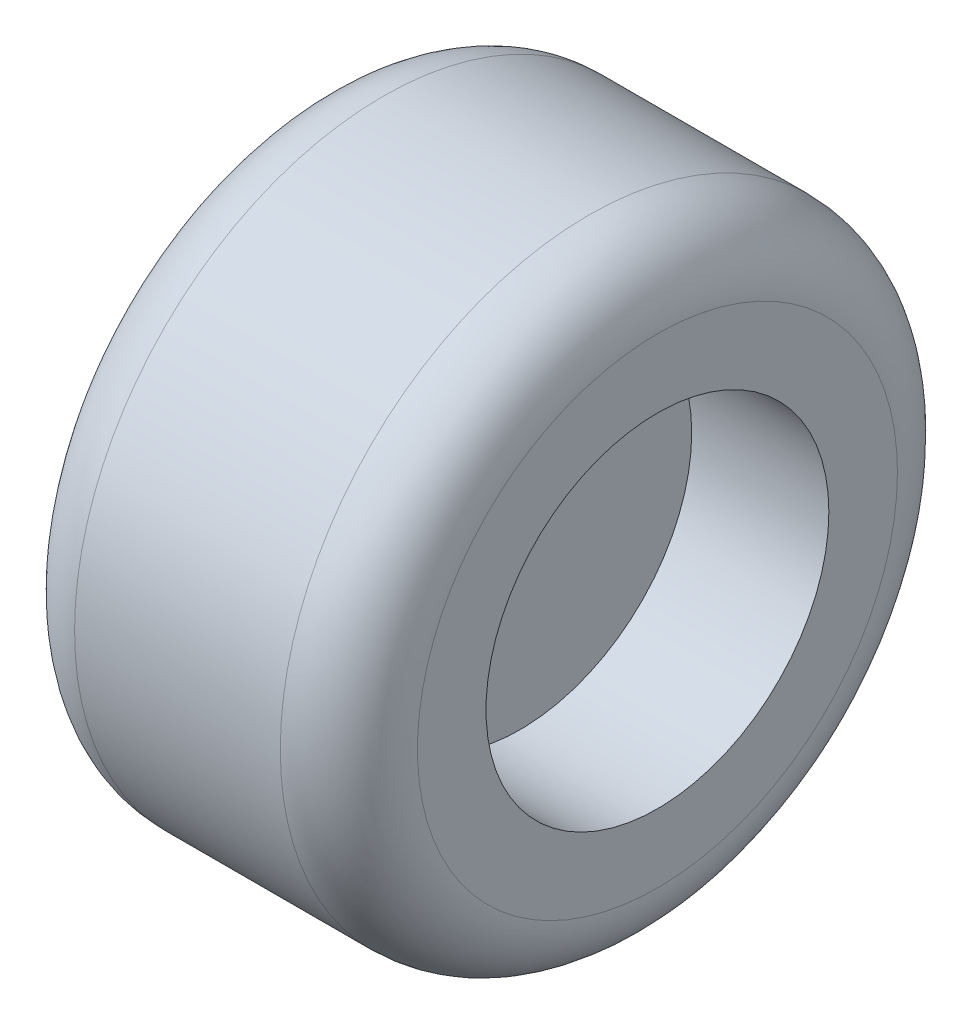
SolidWorks part; units mm, degrees
ref_plane "Front Plane" through (0, 0, 0) normal (0, 0, 1) x (1, 0, 0)
ref_plane "Top Plane" through (0, 0, 0) normal (0, 1, 0) x (1, 0, 0)
ref_plane "Right Plane" through (0, 0, 0) normal (1, 0, 0) x (0, 0, -1)
sketch "Sketch1" plane through (0, 0, 0) normal (1, 0, 0) x (0, 0, -1)
  circle A0 centre (0, 0) radius 22.5
  dimension "D1" = 45
extrude "Boss-Extrude1" add sketch "Sketch1" along normal blind 25
sketch "Sketch2" plane through (25, 0, 0) normal (1, 0, 0) x (0, 0, -1)
  circle A0 centre (0, 0) radius 12.5
  circle A1 centre (0, 0) radius 22.5 construction
  dimension "D1" = 10
extrude "Cut-Extrude1" cut sketch "Sketch2" against normal blind 10
fillet "Fillet1" radius 5 2 edges at (0, 0, -22.5) (25, 0, -22.5)
sketch "Sketch3" plane through (0, 0, 0) normal (-1, 0, 0) x (0, 0, 1)
  circle A0 centre (0, 0) radius 1.5
  dimension "D1" = 3
extrude "Cut-Extrude2" cut sketch "Sketch3" against normal through all
